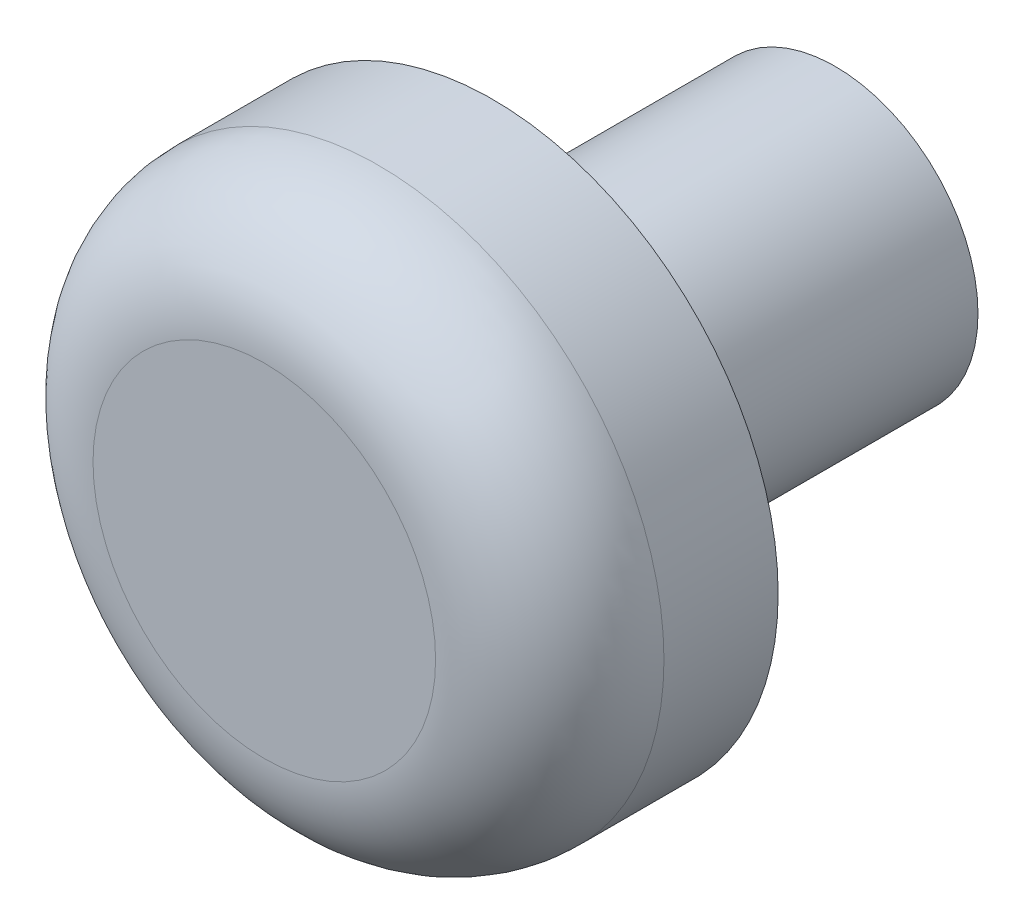
SolidWorks part; units mm, degrees
material "AISI 1045 Steel, cold drawn"
ref_plane "Front Plane" through (0, 0, 0) normal (0, 0, 1) x (1, 0, 0)
ref_plane "Top Plane" through (0, 0, 0) normal (0, 1, 0) x (1, 0, 0)
ref_plane "Right Plane" through (0, 0, 0) normal (1, 0, 0) x (0, 0, -1)
sketch "Sketch1" plane through (0, 0, 0) normal (0, 0, 1) x (1, 0, 0)
  circle A0 centre (0, 0) radius 1.25
  dimension "D1" = 2.5
extrude "Boss-Extrude1" add sketch "Sketch1" along normal blind 3
sketch "Sketch2" plane through (0, 0, 3) normal (0, 0, 1) x (1, 0, 0)
  circle A0 centre (0, 0) radius 2.5
extrude "Boss-Extrude2" add sketch "Sketch2" along normal blind 2
fillet "Fillet1" radius 1 1 edges at (2.5, 0, 5)
